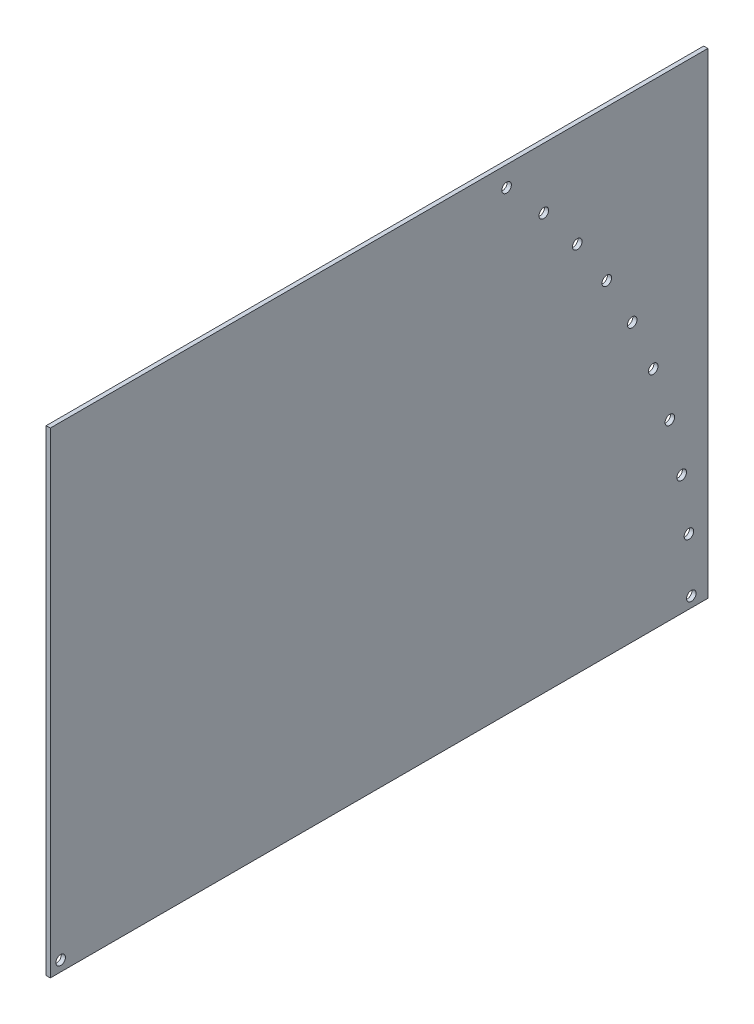
SolidWorks part; units mm, degrees
ref_plane "Front Plane" through (0, 0, 0) normal (0, 0, 1) x (1, 0, 0)
ref_plane "Top Plane" through (0, 0, 0) normal (0, 1, 0) x (1, 0, 0)
ref_plane "Right Plane" through (0, 0, 0) normal (1, 0, 0) x (0, 0, -1)
sketch "Sketch1" plane through (0, 0, 0) normal (1, 0, 0) x (0, 0, -1)
  line L0 (6.35, 6.35) -> (391.75, 6.35) construction
  line L1 (0, 0) -> (401.8692, 0)
  line L2 (0, 0) -> (0, 291.0622)
  line L3 (0, 291.0622) -> (401.8692, 291.0622)
  line L4 (401.8692, 0) -> (401.8692, 291.0622)
  line L5 (6.35, 6.35) -> (390.2834, 39.9398) construction
  line L6 (6.35, 6.35) -> (385.8949, 73.274) construction
  line L7 (6.35, 6.35) -> (378.6178, 106.0989) construction
  line L8 (6.35, 6.35) -> (368.5075, 138.1646) construction
  line L9 (6.35, 6.35) -> (355.641, 169.2271) construction
  line L10 (6.35, 6.35) -> (340.1162, 199.05) construction
  line L11 (6.35, 6.35) -> (322.0512, 227.4064) construction
  line L12 (6.35, 6.35) -> (301.5835, 254.0803) construction
  line L13 (6.35, 6.35) -> (278.8689, 278.8689) construction
  circle A0 centre (6.35, 6.35) radius 2.921
  circle A1 centre (391.75, 6.35) radius 2.921
  circle A2 centre (390.2834, 39.9398) radius 2.921
  circle A3 centre (385.8949, 73.274) radius 2.921
  circle A4 centre (378.6178, 106.0989) radius 2.921
  circle A5 centre (368.5075, 138.1646) radius 2.921
  circle A6 centre (355.641, 169.2271) radius 2.921
  circle A7 centre (340.1162, 199.05) radius 2.921
  circle A8 centre (322.0512, 227.4064) radius 2.921
  circle A9 centre (301.5835, 254.0803) radius 2.921
  circle A10 centre (278.8689, 278.8689) radius 2.921
  point P17 (6.35, 9.271)
  point P20 (6.35, 0)
  point P23 (9.271, 6.35)
  point P26 (6.35, 3.429)
  point P29 (0, 0)
  point P32 (9.271, 6.35)
  dimension "D1" = 5.842
  dimension "D2" = 6.35
  dimension "D3" = 6.35
  dimension "D4" = 385.4
  dimension "D5" = 5
  dimension "D6" = 5
  dimension "D7" = 5
  dimension "D8" = 5
  dimension "D9" = 5
  dimension "D10" = 5
  dimension "D11" = 5
  dimension "D12" = 5
  dimension "D13" = 5
  dimension "D14" = 401.8692
  dimension "D15" = 291.0622
extrude "Boss-Extrude1" add sketch "Sketch1" along normal blind 2.54
sketch "Sketch2" plane through (2.54, 0, 0) normal (1, 0, 0) x (0, 0, -1)
  line L0 (6.35, 6.35) -> (391.75, 6.35) construction
  line L1 (6.35, 6.35) -> (385.8949, 73.274) construction
  line L2 (6.35, 6.35) -> (368.5075, 138.1646) construction
  line L3 (6.35, 6.35) -> (340.1162, 199.05) construction
  line L4 (6.35, 6.35) -> (301.5835, 254.0803) construction
  point P4 (373.6074, 67.6306)
  point P7 (180.4881, 6.35)
  point P9 (188.4069, 42.3165)
  point P10 (190.8913, 64.0543)
  point P11 (183.9041, 92.1583)
  point P12 (172.7246, 106.5985)
  point P13 (391.75, 6.35)
  point P15 (0, 0)
  point P16 (357.764, 130.1242)
  point P17 (327.8374, 187.7769)
  point P18 (295.2703, 246.7498)
  point P19 (385.8949, 73.274)
  point P21 (368.5075, 138.1646)
  point P23 (340.1162, 199.05)
  point P25 (301.5835, 254.0803)
